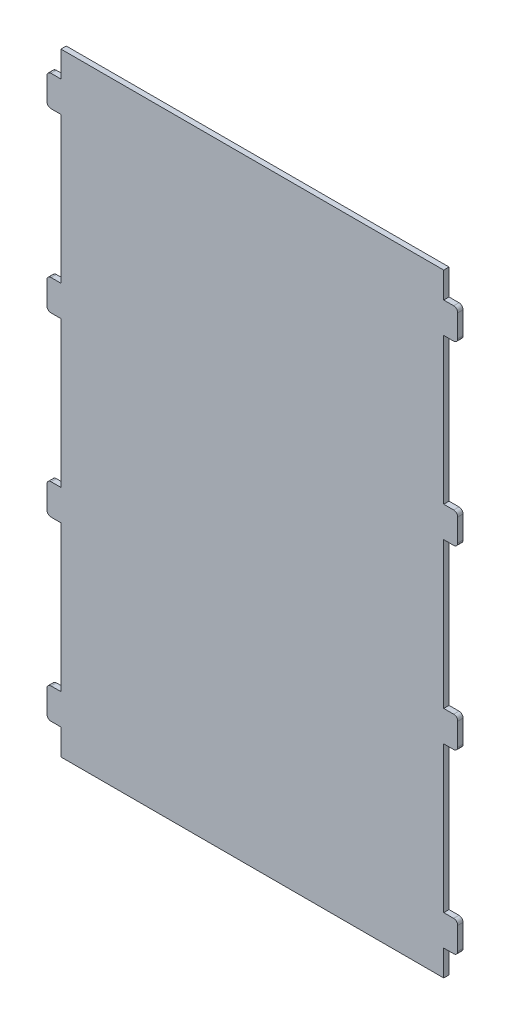
SolidWorks part; units mm, degrees
ref_plane "Front Plane" through (0, 0, 0) normal (0, 0, 1) x (1, 0, 0)
ref_plane "Top Plane" through (0, 0, 0) normal (0, 1, 0) x (1, 0, 0)
ref_plane "Right Plane" through (0, 0, 0) normal (1, 0, 0) x (0, 0, -1)
sketch "Model" plane through (0, 0, 0) normal (0, 0, 1) x (1, 0, 0)
  line L0 (93.65, 50.7667) -> (93.65, 122.3)
  line L1 (93.65, 50.7667) -> (98.51, 50.7667)
  line L2 (100.51, 48.7667) -> (100.51, 37.7667)
  line L3 (98.51, 35.7667) -> (93.65, 35.7667)
  line L4 (93.65, -35.7667) -> (93.65, 35.7667)
  line L5 (93.65, -35.7667) -> (98.51, -35.7667)
  line L6 (100.51, -37.7667) -> (100.51, -48.7667)
  line L7 (98.51, -50.7667) -> (93.65, -50.7667)
  line L8 (93.65, -122.3) -> (93.65, -50.7667)
  line L9 (93.65, -122.3) -> (98.51, -122.3)
  line L10 (100.51, -124.3) -> (100.51, -135.3)
  line L11 (98.51, -137.3) -> (93.65, -137.3)
  line L12 (93.65, -150) -> (93.65, -137.3)
  line L13 (-93.65, -150) -> (93.65, -150)
  line L14 (-93.65, -137.3) -> (-93.65, -150)
  line L15 (-98.51, -137.3) -> (-93.65, -137.3)
  line L16 (-100.51, -124.3) -> (-100.51, -135.3)
  line L17 (-93.65, -122.3) -> (-98.51, -122.3)
  line L18 (-93.65, -50.7667) -> (-93.65, -122.3)
  line L19 (-98.51, -50.7667) -> (-93.65, -50.7667)
  line L20 (-100.51, -37.7667) -> (-100.51, -48.7667)
  line L21 (-93.65, -35.7667) -> (-98.51, -35.7667)
  line L22 (-93.65, 35.7667) -> (-93.65, -35.7667)
  line L23 (-98.51, 35.7667) -> (-93.65, 35.7667)
  line L24 (-100.51, 48.7667) -> (-100.51, 37.7667)
  line L25 (-93.65, 50.7667) -> (-98.51, 50.7667)
  line L26 (-93.65, 122.3) -> (-93.65, 50.7667)
  line L27 (-98.51, 122.3) -> (-93.65, 122.3)
  line L28 (-100.51, 135.3) -> (-100.51, 124.3)
  line L29 (-93.65, 137.3) -> (-98.51, 137.3)
  line L30 (-93.65, 150) -> (-93.65, 137.3)
  line L31 (93.65, 150) -> (-93.65, 150)
  line L32 (93.65, 137.3) -> (93.65, 150)
  line L33 (93.65, 137.3) -> (98.51, 137.3)
  line L34 (100.51, 135.3) -> (100.51, 124.3)
  line L35 (98.51, 122.3) -> (93.65, 122.3)
  arc A0 (100.51, 48.7667) -> (98.51, 50.7667) centre (98.51, 48.7667) ccw
  arc A1 (98.51, 35.7667) -> (100.51, 37.7667) centre (98.51, 37.7667) ccw
  arc A2 (100.51, -37.7667) -> (98.51, -35.7667) centre (98.51, -37.7667) ccw
  arc A3 (98.51, -50.7667) -> (100.51, -48.7667) centre (98.51, -48.7667) ccw
  arc A4 (100.51, -124.3) -> (98.51, -122.3) centre (98.51, -124.3) ccw
  arc A5 (98.51, -137.3) -> (100.51, -135.3) centre (98.51, -135.3) ccw
  arc A6 (-100.51, -135.3) -> (-98.51, -137.3) centre (-98.51, -135.3) ccw
  arc A7 (-98.51, -122.3) -> (-100.51, -124.3) centre (-98.51, -124.3) ccw
  arc A8 (-100.51, -48.7667) -> (-98.51, -50.7667) centre (-98.51, -48.7667) ccw
  arc A9 (-98.51, -35.7667) -> (-100.51, -37.7667) centre (-98.51, -37.7667) ccw
  arc A10 (-100.51, 37.7667) -> (-98.51, 35.7667) centre (-98.51, 37.7667) ccw
  arc A11 (-98.51, 50.7667) -> (-100.51, 48.7667) centre (-98.51, 48.7667) ccw
  arc A12 (-100.51, 124.3) -> (-98.51, 122.3) centre (-98.51, 124.3) ccw
  arc A13 (-98.51, 137.3) -> (-100.51, 135.3) centre (-98.51, 135.3) ccw
  arc A14 (100.51, 135.3) -> (98.51, 137.3) centre (98.51, 135.3) ccw
  arc A15 (98.51, 122.3) -> (100.51, 124.3) centre (98.51, 124.3) ccw
extrude "Boss-Extrude1" add sketch "Model" along normal blind 2.6
